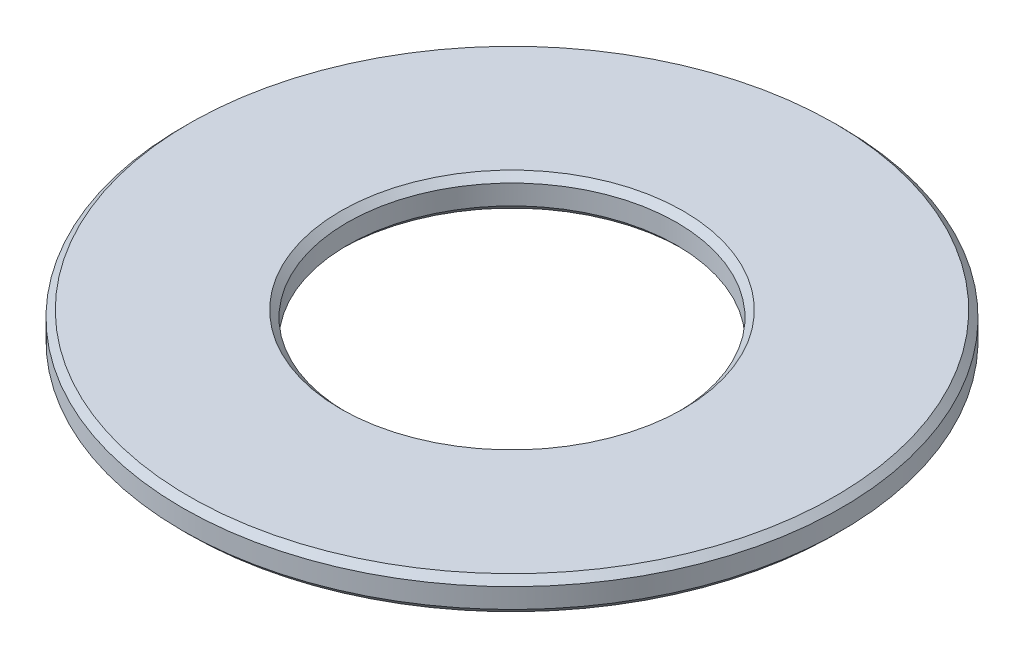
SolidWorks part; units mm, degrees
ref_plane "前视基准面" through (0, 0, 0) normal (0, 0, 1) x (1, 0, 0)
ref_plane "上视基准面" through (0, 0, 0) normal (0, 1, 0) x (1, 0, 0)
ref_plane "右视基准面" through (0, 0, 0) normal (1, 0, 0) x (0, 0, -1)
sketch "草图2" plane through (0, 0, 0) normal (0, 1, 0) x (1, 0, 0)
  circle A0 centre (0, 0) radius 5
  circle A1 centre (0, 0) radius 10
  dimension "D1" = 10
  dimension "D2" = 20
extrude "凸台-拉伸1" add sketch "草图2" along normal mid plane 1
chamfer "倒角1" distance 0.2 angle 45 4 edges at (0, -0.5, 5) (0, 0.5, 5) (0, -0.5, 10) (0, 0.5, 10)
